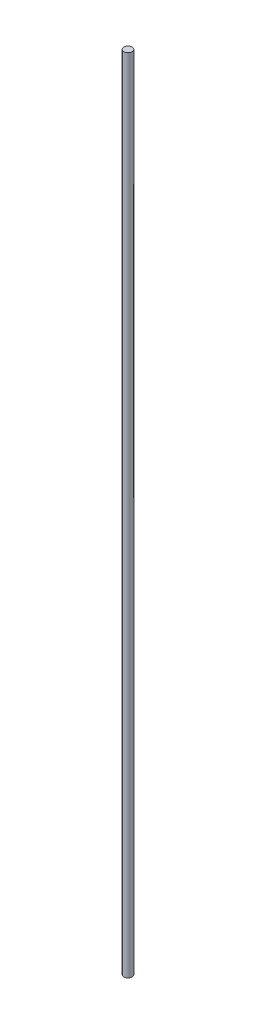
SolidWorks part; units mm, degrees
ref_plane "Front Plane" through (0, 0, 0) normal (0, 0, 1) x (1, 0, 0)
ref_plane "Top Plane" through (0, 0, 0) normal (0, 1, 0) x (1, 0, 0)
ref_plane "Right Plane" through (0, 0, 0) normal (1, 0, 0) x (0, 0, -1)
sketch "Sketch1" plane through (0, 0, 0) normal (0, 1, 0) x (1, 0, 0)
  circle A0 centre (0, 0) radius 3.175
  dimension "D1" = 6.35
extrude "Boss-Extrude1" add sketch "Sketch1" along normal blind 617.22
